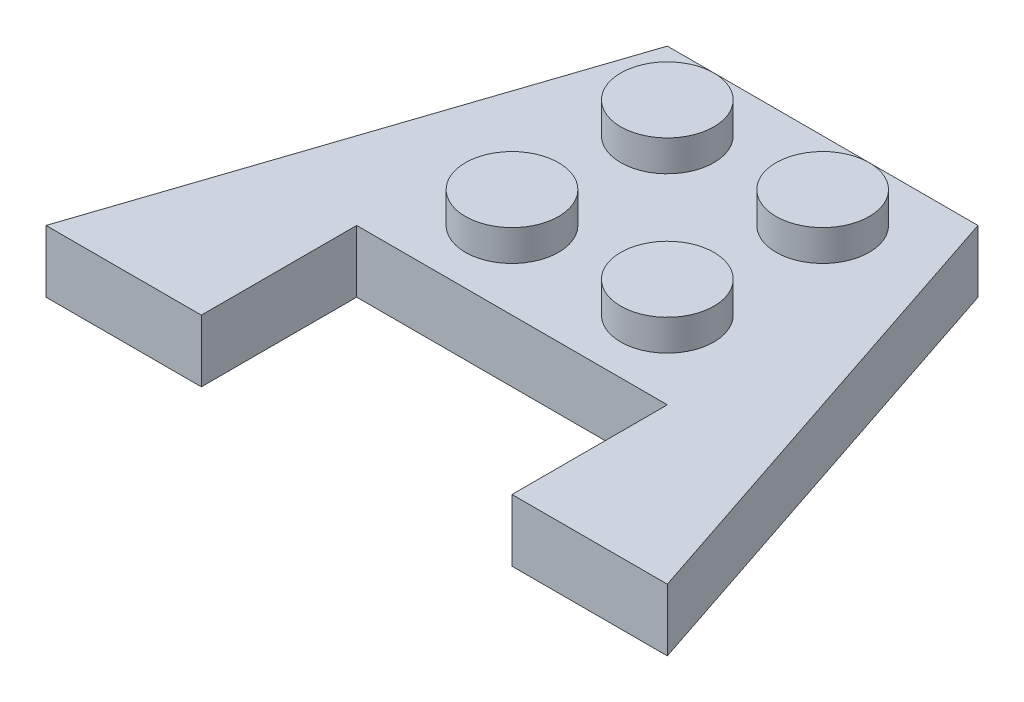
SolidWorks part; units mm, degrees
ref_plane "Front Plane" through (0, 0, 0) normal (0, 0, 1) x (1, 0, 0)
ref_plane "Top Plane" through (0, 0, 0) normal (0, 1, 0) x (1, 0, 0)
ref_plane "Right Plane" through (0, 0, 0) normal (1, 0, 0) x (0, 0, -1)
sketch "Sketch1" plane through (0, 0, 0) normal (0, 1, 0) x (1, 0, 0)
  line L0 (0, 0) -> (8, 24)
  line L1 (8, 24) -> (24, 24)
  line L2 (24, 24) -> (32, 0)
  line L4 (0, 0) -> (8, 0)
  line L5 (8, 0) -> (8, 8)
  line L6 (8, 8) -> (24, 8)
  line L7 (24, 8) -> (24, 0)
  line L8 (24, 0) -> (32, 0)
  dimension "D1" = 8
  dimension "D2" = 8
  dimension "D3" = 24
  dimension "D4" = 8
  dimension "D5" = 8
  dimension "D6" = 16
  dimension "D7" = 16
extrude "Boss-Extrude1" add sketch "Sketch1" along normal blind 3.2
sketch "Sketch2" plane through (0, 3.2, 0) normal (0, 1, 0) x (1, 0, 0)
  line L0 (8, 24) -> (12, 24) construction
  line L1 (24, 24) -> (8, 24) construction
  line L2 (12, 24) -> (12, 20) construction
  circle A0 centre (12, 20) radius 2.4
  dimension "D3" = 4.8
  dimension "D1" = 4
  dimension "D2" = 4
extrude "Boss-Extrude2" add sketch "Sketch2" along normal blind 1.6
pattern_linear "LPattern1" count 2 spacing 8 along (1, 0, 0) count 2 spacing 8 along (0, 0, 1) of "Boss-Extrude2"
shell "Shell1" thickness 1.6
